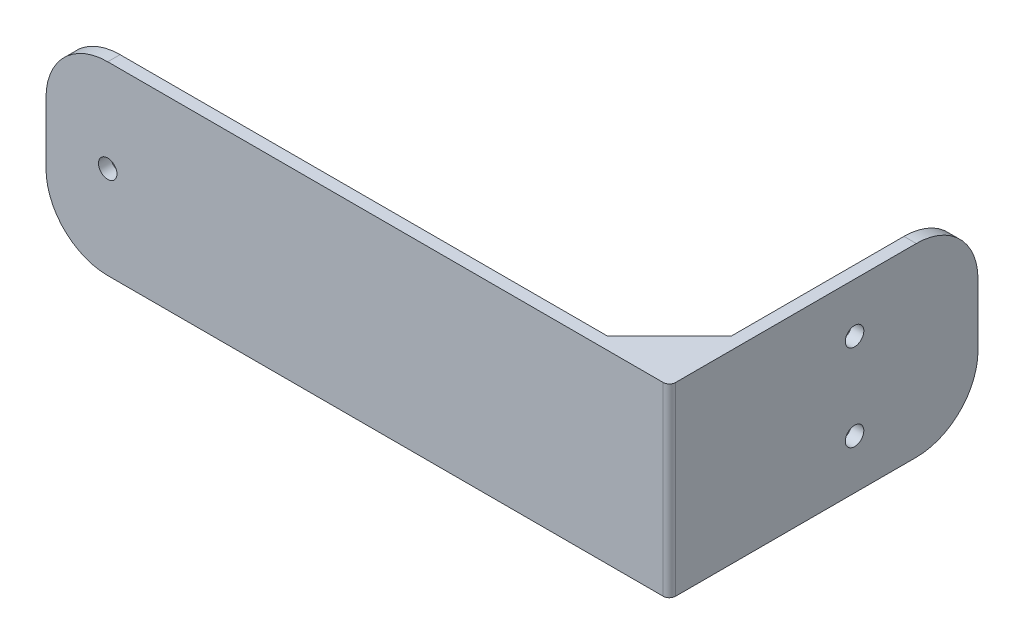
SolidWorks part; units mm, degrees
ref_plane "Front Plane" through (0, 0, 0) normal (0, 0, 1) x (1, 0, 0)
ref_plane "Top Plane" through (0, 0, 0) normal (0, 1, 0) x (1, 0, 0)
ref_plane "Right Plane" through (0, 0, 0) normal (1, 0, 0) x (0, 0, -1)
sketch "Sketch1" plane through (0, 0, 0) normal (0, 0, 1) x (1, 0, 0)
  line L1 (0, 0) -> (100, 0)
  line L2 (0, 0) -> (0, 30)
  line L3 (0, 30) -> (100, 30)
  line L4 (100, 0) -> (100, 30)
  circle A0 centre (10, 15) radius 1.5
  dimension "D3" = 15
  dimension "D4" = 10
  dimension "D1" = 30
  dimension "D2" = 100
extrude "Boss-Extrude1" add sketch "Sketch1" along normal blind 2
sketch "Sketch2" plane through (0, 0, 2) normal (0, 0, 1) x (1, 0, 0)
  line L0 (0, 0) -> (100, 0) construction
  line L1 (100, 30) -> (101, 30)
  line L2 (100, 30) -> (100, 0)
  line L3 (100, 0) -> (101, 0)
  line L4 (101, 30) -> (101, 0)
  line L5 (100, 30) -> (99, 30)
  line L6 (100, 30) -> (100, 0)
  line L7 (100, 0) -> (99, 0)
  line L8 (99, 30) -> (99, 0)
  line M2 (0, 0) -> (100, 0)
  line M3 (100, 0) -> (100, 30)
  line M4 (100, 30) -> (0, 30)
  dimension "D1" = 1
  dimension "D2" = 1
extrude "Boss-Extrude3" add sketch "Sketch2" against normal blind 50 contours L4 L1 L3 M3 | L8 M4 M2 M3
fillet "Fillet2" radius 1 2 edges at (101, 15, 2) (99, 15, 0)
sketch "Sketch3" plane through (101, 0, 0) normal (1, 0, 0) x (0, 0, -1)
  line L0 (48, 15) -> (28, 15)
  line L1 (48, 30) -> (48, 0) construction
  line L2 (28, 15) -> (28, 8)
  line L3 (28, 15) -> (28, 22)
  circle A0 centre (28, 8) radius 1.5
  circle A1 centre (28, 22) radius 1.5
  dimension "D1" = 7
  dimension "D2" = 7
extrude "Cut-Extrude1" cut sketch "Sketch3" against normal blind 10
fillet "Fillet3" radius 10 4 edges at (0, 30, 1) (0, 0, 1) (100, 0, -48) (100, 30, -48)
ref_plane "Plane1" through (0, 15, 0) normal (0, 1, 0) x (1, 0, 0)
sketch "Sketch4" plane through (0, 0, 0) normal (0, 1, 0) x (1, 0, 0)
  line L0 (10, 0) -> (98, 0) construction
  line L1 (89, 0) -> (99, 0)
  line L2 (89, 0) -> (89, 10)
  line L3 (89, 10) -> (99, 10)
  line L4 (99, 0) -> (99, 10)
  line L5 (99, 38) -> (99, 1) construction
  line L6 (89, 0) -> (99, 10)
  circle A0 centre (98, 1) radius 1
  dimension "D1" = 10
  dimension "D2" = 10
extrude "Boss-Extrude4" add sketch "Sketch4" along normal blind 2 contours A0 L4 L3 L2 L1 | A0
mirror "Mirror1" about plane through (0, 15, 0) normal (0, 1, 0) of "Boss-Extrude4"
